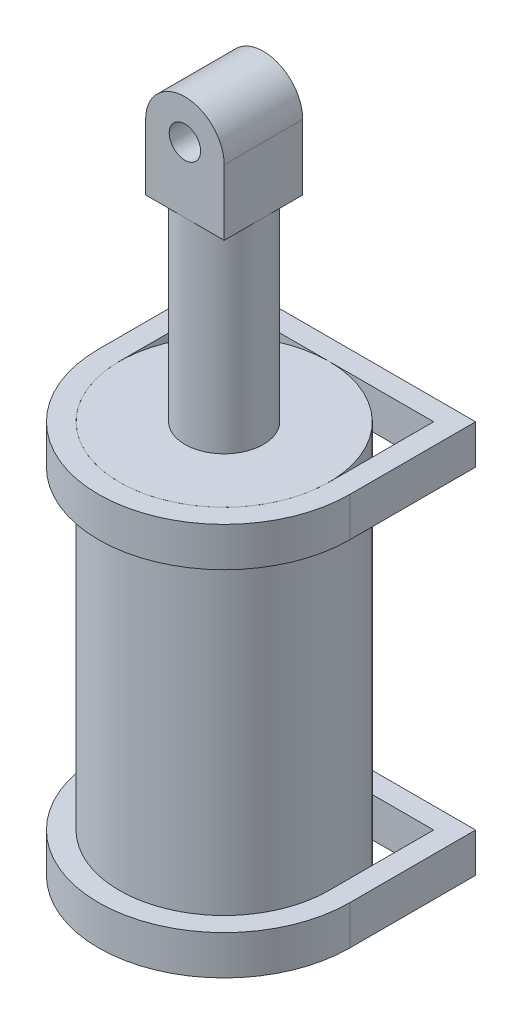
SolidWorks part; units mm, degrees
ref_plane "Front Plane" through (0, 0, 0) normal (0, 0, 1) x (1, 0, 0)
ref_plane "Top Plane" through (0, 0, 0) normal (0, 1, 0) x (1, 0, 0)
ref_plane "Right Plane" through (0, 0, 0) normal (1, 0, 0) x (0, 0, -1)
sketch "Sketch1" plane through (0, 0, 0) normal (0, 1, 0) x (1, 0, 0)
  circle A0 centre (0, 0) radius 40
  dimension "D1" = 80
extrude "Boss-Extrude1" add sketch "Sketch1" along normal mid plane 150
sketch "Sketch2" plane through (0, 75, 0) normal (0, 1, 0) x (1, 0, 0)
  circle A0 centre (0, 0) radius 15
  dimension "D1" = 30
extrude "Boss-Extrude2" add sketch "Sketch2" along normal blind 75
sketch "Sketch3" plane through (0, 150, 0) normal (0, 1, 0) x (1, 0, 0)
  line L1 (-15, 15) -> (15, 15)
  line L2 (-15, 15) -> (-15, -15)
  line L3 (-15, -15) -> (15, -15)
  line L4 (15, 15) -> (15, -15)
  line L5 (-15, 15) -> (15, -15) construction
  line L6 (-15, -15) -> (15, 15) construction
  circle A0 centre (0, 0) radius 15 construction
  point P0 (0, 0)
extrude "Boss-Extrude3" add sketch "Sketch3" along normal blind 25
sketch "Sketch4" plane through (0, 0, 15) normal (0, 0, 1) x (1, 0, 0)
  line L0 (-15, 175) -> (15, 175) construction
  line L1 (-15, 175) -> (15, 175)
  arc A0 (-15, 175) -> (15, 175) centre (0, 175) cw
extrude "Boss-Extrude4" add sketch "Sketch4" against normal up to vertex (30 mm away)
sketch "Sketch5" plane through (0, 0, 15) normal (0, 0, 1) x (1, 0, 0)
  circle A0 centre (0, 175) radius 6
  dimension "D1" = 12
extrude "Cut-Extrude1" cut sketch "Sketch5" against normal through all both and the other way through all
sketch "Sketch6" plane through (0, -75, 0) normal (0, -1, 0) x (1, 0, 0)
  line L0 (-48, 0) -> (-48, -40)
  line L7 (48, -40) -> (48, 0)
  line L8 (-40, 0) -> (-40, -40)
  line L9 (-40, -40) -> (40, -40)
  line L10 (40, -40) -> (40, 0)
  line L14 (40, -48) -> (0, -48)
  line L15 (40, -48) -> (58, -48)
  line L16 (58, -48) -> (58, -40)
  line L17 (58, -40) -> (48, -40)
  line L18 (-48, -40) -> (-48, -58)
  line L19 (-48, -58) -> (-40, -58)
  line L20 (-40, -58) -> (-40, -48)
  line L21 (-40, -48) -> (0, -48)
  circle A0 centre (0, 0) radius 40 construction
  arc A1 (40, 0) -> (-40, 0) centre (0, 0) ccw
  arc A2 (48, 0) -> (-48, 0) centre (0, 0) ccw
  dimension "D1" = 8
  dimension "D2" = 48
  dimension "D3" = 18
  dimension "D5" = 10
extrude "Boss-Extrude6" add sketch "Sketch6" against normal blind 15 separate body
sketch "Sketch7" plane through (0, 75, 0) normal (0, 1, 0) x (1, 0, 0)
  line L0 (40, 40) -> (40, 0) construction
  line L1 (-40, 0) -> (-40, 40) construction
  line L2 (-40, 40) -> (40, 40) construction
  line L3 (40, 40) -> (40, 0)
  line L4 (-40, 0) -> (-40, 40)
  line L5 (-40, 40) -> (40, 40)
  line L7 (48, 0) -> (48, 40)
  line L8 (48, 40) -> (58, 40)
  line L9 (58, 40) -> (58, 48)
  line L10 (48, 40) -> (58, 40)
  line L11 (58, 48) -> (-40, 48)
  line L12 (58, 48) -> (-40, 48)
  line L13 (-48, 58) -> (-48, 0)
  line L14 (48, 0) -> (48, 40)
  line L16 (58, 40) -> (58, 48)
  line L20 (-48, 58) -> (-48, 0)
  line L28 (-40, 48) -> (-40, 58)
  line L29 (-40, 48) -> (-40, 58)
  line L30 (-40, 58) -> (-48, 58)
  line L31 (-40, 58) -> (-48, 58)
  arc A0 (-40, 0) -> (40, 0) centre (0, 0) ccw construction
  arc A1 (-48, 0) -> (48, 0) centre (0, 0) ccw
  arc A2 (-48, 0) -> (48, 0) centre (0, 0) ccw
  arc A3 (-40, 0) -> (40, 0) centre (0, 0) ccw
  dimension "D1" = 0
extrude "Boss-Extrude8" add sketch "Sketch7" against normal blind 15 separate body
sketch "Sketch8" plane through (-40, 0, 0) normal (1, 0, 0) x (0, 0, -1)
  line L0 (48, -75) -> (58, -75)
  line L1 (58, -75) -> (58, -60)
  line L2 (58, -60) -> (48, -60)
  line L3 (48, -60) -> (48, -75)
extrude "Cut-Extrude2" cut sketch "Sketch8" against normal blind 10
sketch "Sketch9" plane through (-40, 0, 0) normal (1, 0, 0) x (0, 0, -1)
  line L0 (48, 60) -> (58, 60)
  line L1 (58, 60) -> (58, 75)
  line L2 (58, 75) -> (48, 75)
  line L3 (48, 75) -> (48, 60)
extrude "Cut-Extrude3" cut sketch "Sketch9" against normal blind 10
sketch "Sketch10" plane through (0, 0, -40) normal (0, 0, 1) x (1, 0, 0)
  line L0 (48, 60) -> (58, 60)
  line L1 (58, 60) -> (58, 75)
  line L2 (58, 75) -> (48, 75)
  line L3 (48, 75) -> (48, 60)
extrude "Cut-Extrude4" cut sketch "Sketch10" against normal blind 10
sketch "Sketch11" plane through (0, 0, -40) normal (0, 0, 1) x (1, 0, 0)
  line L0 (48, -75) -> (48, -60)
  line L1 (48, -60) -> (58, -60)
  line L2 (58, -60) -> (58, -75)
  line L3 (58, -75) -> (48, -75)
extrude "Cut-Extrude5" cut sketch "Sketch11" against normal blind 10
